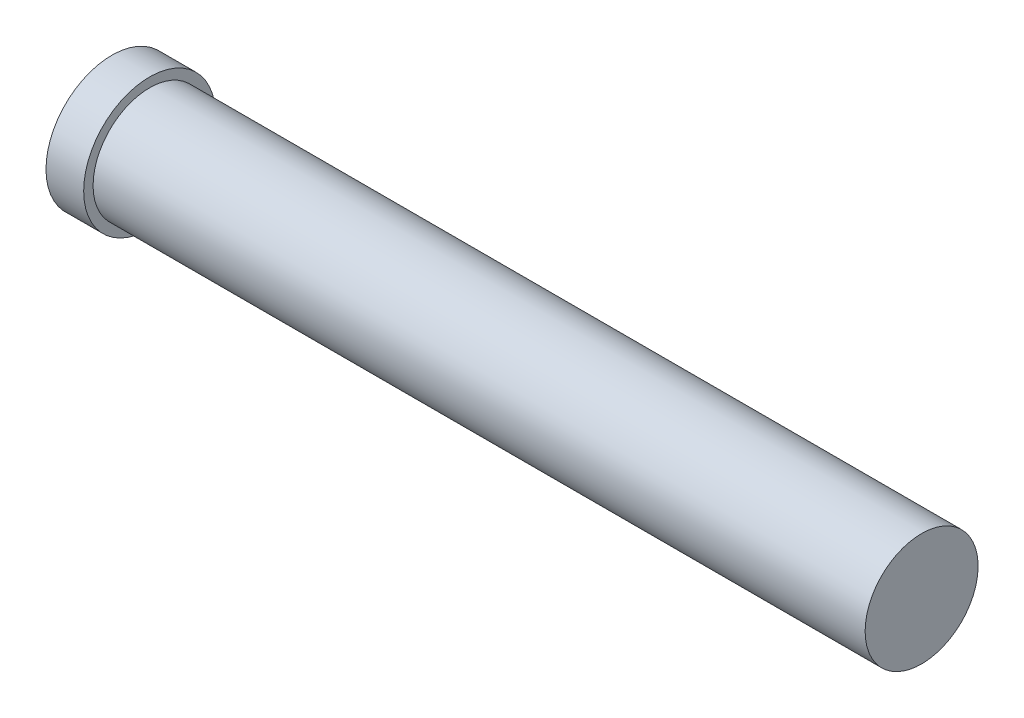
SolidWorks part; units mm, degrees
material "AISI 1020"
ref_plane "Ön Düzlem" through (0, 0, 0) normal (0, 0, 1) x (1, 0, 0)
ref_plane "Üst Düzlem" through (0, 0, 0) normal (0, 1, 0) x (1, 0, 0)
ref_plane "Sağ Düzlem" through (0, 0, 0) normal (1, 0, 0) x (0, 0, -1)
sketch "Çizim1" plane through (0, 0, 0) normal (0, 0, 1) x (1, 0, 0)
  line L0 (0, 0) -> (430, 0) construction
  line L1 (0, 0) -> (0, 35)
  line L2 (0, 35) -> (20, 35)
  line L3 (20, 35) -> (20, 30)
  line L4 (20, 30) -> (430, 30)
  line L5 (430, 30) -> (430, 0)
  line L6 (0, 0) -> (430, 0)
  dimension "D1" = 430
  dimension "D2" = 20
  dimension "D3" = 5
  dimension "D4" = 30
revolve "Döndür1" add sketch "Çizim1" angle 360 about L0
